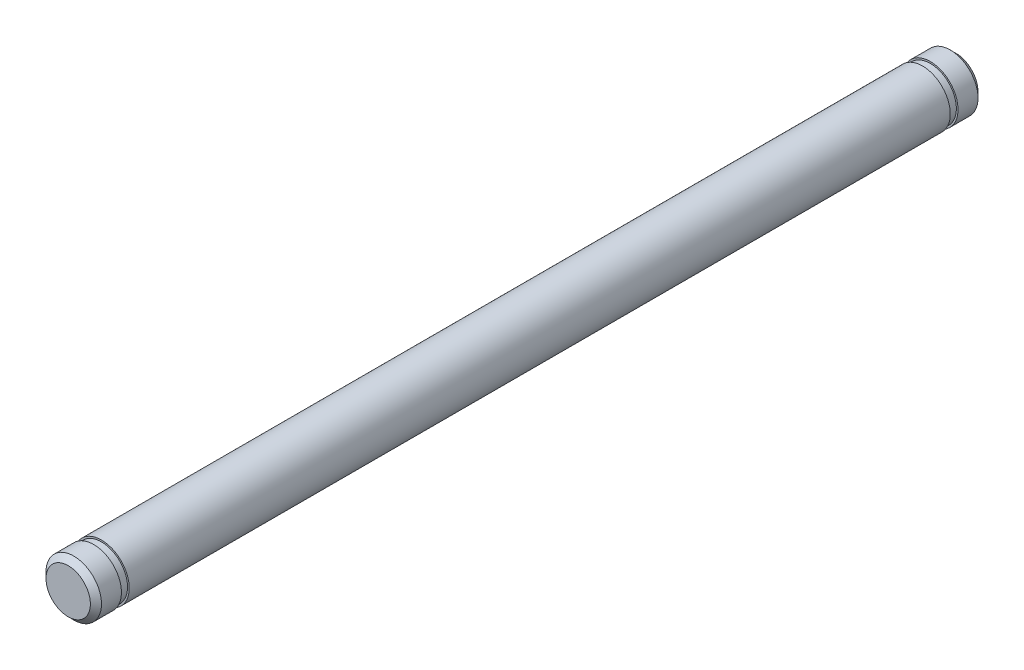
SolidWorks part; units mm, degrees
ref_plane "前视基准面" through (0, 0, 0) normal (0, 0, 1) x (1, 0, 0)
ref_plane "上视基准面" through (0, 0, 0) normal (0, 1, 0) x (1, 0, 0)
ref_plane "右视基准面" through (0, 0, 0) normal (1, 0, 0) x (0, 0, -1)
other "Configuration Table"
sketch "草图1" plane through (0, 0, 0) normal (0, 0, 1) x (1, 0, 0)
  circle A0 centre (0, 0) radius 2.5
  dimension "D1" = 5
extrude "凸台-拉伸1" add sketch "草图1" along normal blind 80
chamfer "倒角1" distance 0.5 angle 45 2 edges at (2.5, 0, 80) (2.5, 0, 0)
ref_plane "基准面1" through (0, 0, 40) normal (0, 0, 1) x (1, 0, 0)
sketch "草图2" plane through (0, 0, 0) normal (0, 0, -1) x (-1, 0, 0)
  circle A0 centre (0, 0) radius 2.5 construction
  circle A1 centre (0, 0) radius 2.5
  circle A2 centre (0, 0) radius 2.35
  dimension "D1" = 4.7
extrude "切除-拉伸1" cut sketch "草图2" along normal blind 0.7 from offset 3 offset against normal yes
mirror "镜向1" about plane through (0, 0, 40) normal (0, 0, 1) of "切除-拉伸1"
